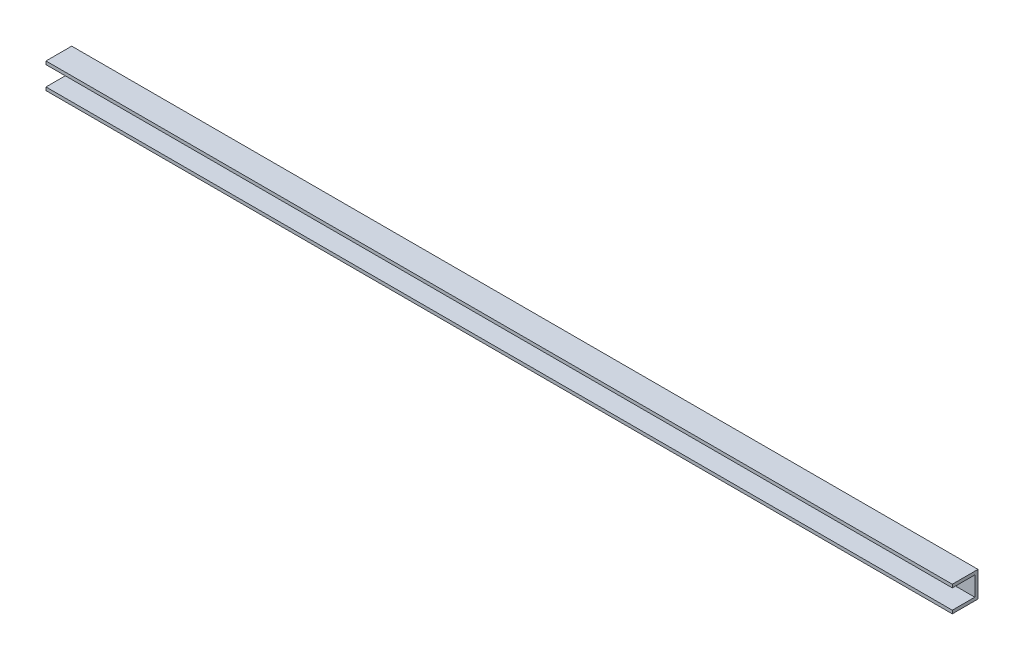
SolidWorks part; units mm, degrees
ref_plane "Front Plane" through (0, 0, 0) normal (0, 0, 1) x (1, 0, 0)
ref_plane "Top Plane" through (0, 0, 0) normal (0, 1, 0) x (1, 0, 0)
ref_plane "Right Plane" through (0, 0, 0) normal (1, 0, 0) x (0, 0, -1)
sketch "Sketch1" plane through (0, 0, 0) normal (1, 0, 0) x (0, 0, -1)
  line L0 (-29.5752, 4.7351) -> (-29.5752, 1.5601)
  line L1 (-29.5752, 1.5601) -> (-7.3502, 1.5601)
  line L2 (-7.3502, 1.5601) -> (-7.3502, -17.4899)
  line L3 (-7.3502, -17.4899) -> (-29.5752, -17.4899)
  line L4 (-29.5752, -17.4899) -> (-29.5752, -20.6649)
  line L5 (-29.5752, -20.6649) -> (-4.1752, -20.6649)
  line L6 (-4.1752, -20.6649) -> (-4.1752, 4.7351)
  line L7 (-4.1752, 4.7351) -> (-29.5752, 4.7351)
  dimension "D1" = 22.225
  dimension "D2" = 22.225
  dimension "D3" = 19.05
  dimension "D4" = 25.4
  dimension "D5" = 3.175
  dimension "D6" = 3.175
  dimension "D7" = 25.4
extrude "Boss-Extrude2" add sketch "Sketch1" along normal blind 895.35
